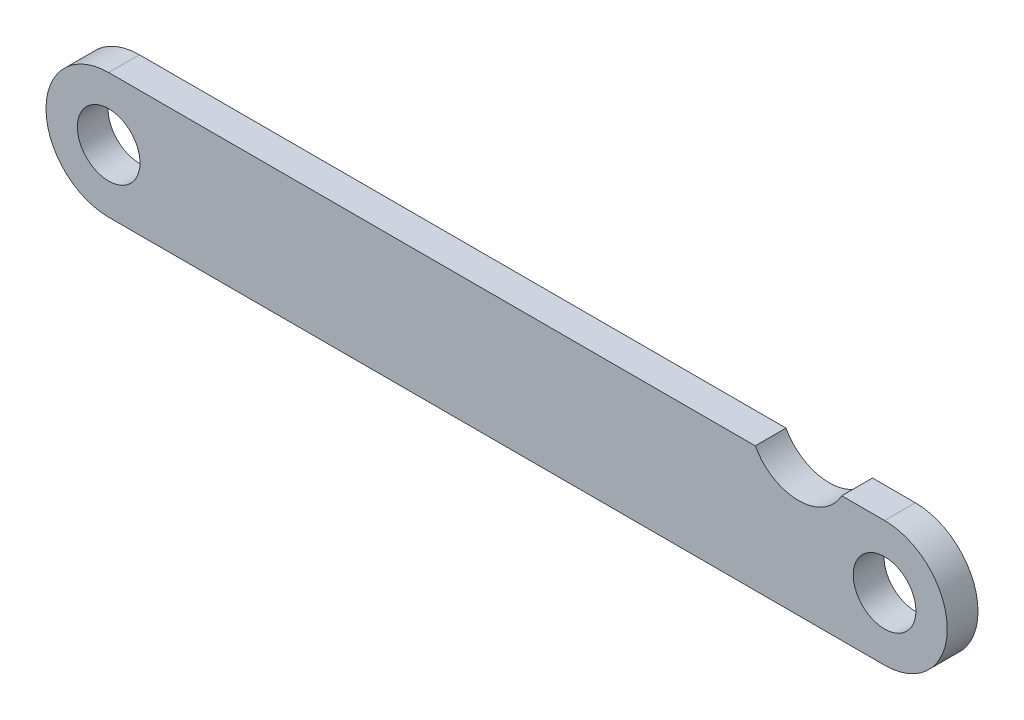
SolidWorks part; units mm, degrees
ref_plane "Спереди" through (0, 0, 0) normal (0, 0, 1) x (1, 0, 0)
ref_plane "Сверху" through (0, 0, 0) normal (0, 1, 0) x (1, 0, 0)
ref_plane "Справа" through (0, 0, 0) normal (1, 0, 0) x (0, 0, -1)
sketch "Sketch1" plane through (0, 0, 0) normal (0, 0, 1) x (1, 0, 0)
  line L0 (0, 0) -> (-25.2343, 0)
  line L1 (-25.2343, 2.038) -> (0, 2.038)
  line L2 (-25.2343, -2.038) -> (0, -2.038)
  circle A0 centre (0, 0) radius 1.019
  circle A1 centre (0, 0) radius 2.038
  circle A2 centre (-25.2343, 0) radius 1.019
  circle A3 centre (-25.2343, 0) radius 2.038
  dimension "D1" = 25.2343
extrude "Extrude1" add sketch "Sketch1" along normal blind 1
sketch "Sketch2" plane through (0, 0, 0) normal (0, 0, 1) x (1, 0, 0)
  line L0 (0, 0) -> (-2.8, 0)
  line L1 (-2.8, 0) -> (-2.8, 2.8)
  circle A0 centre (-2.8, 2.8) radius 1.6
  dimension "D1" = 2.8
  dimension "D2" = 2.8
extrude "Cut-Extrude2" cut sketch "Sketch2" along normal through all
